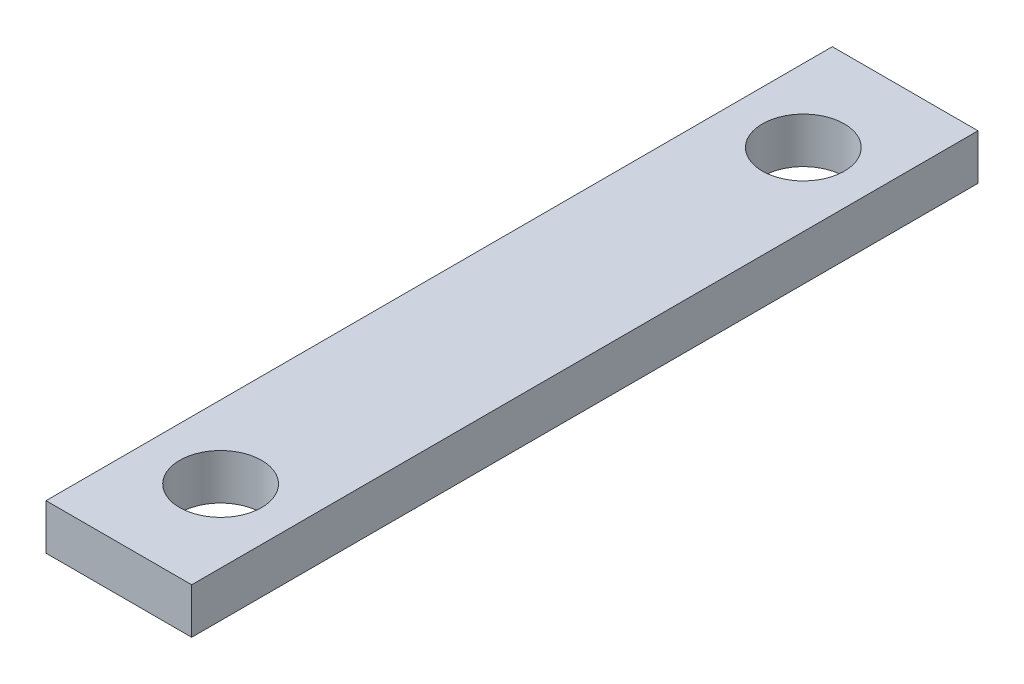
SolidWorks part; units mm, degrees
ref_plane "Front Plane" through (0, 0, 0) normal (0, 0, 1) x (1, 0, 0)
ref_plane "Top Plane" through (0, 0, 0) normal (0, 1, 0) x (1, 0, 0)
ref_plane "Right Plane" through (0, 0, 0) normal (1, 0, 0) x (0, 0, -1)
ref_plane "Plane1" through (0, -24, 0) normal (0, -1, 0) x (-1, 0, 0)
sketch "Sketch1" plane through (0, -24, 0) normal (0, -1, 0) x (-1, 0, 0)
  line L1 (39.37, 21.59) -> (47.37, 21.59)
  line L2 (39.37, 21.59) -> (39.37, -21.59)
  line L3 (39.37, -21.59) -> (47.37, -21.59)
  line L4 (47.37, 21.59) -> (47.37, -21.59)
  line L5 (39.37, 21.59) -> (47.37, -21.59) construction
  line L6 (39.37, -21.59) -> (47.37, 21.59) construction
  line L8 (47.37, -20.875) -> (47.37, 19.6811) construction
  line L10 (39.37, 25.0472) -> (39.37, 22.0897) construction
  circle A1 centre (43.37, -16) radius 2.25
  circle A2 centre (43.37, 16) radius 2.25
  point P0 (43.37, 0)
  point P7 (0, 0)
  dimension "D1" = 4.5
  dimension "D2" = 43.18
extrude "Boss-Extrude1" add sketch "Sketch1" along normal blind 2.5
